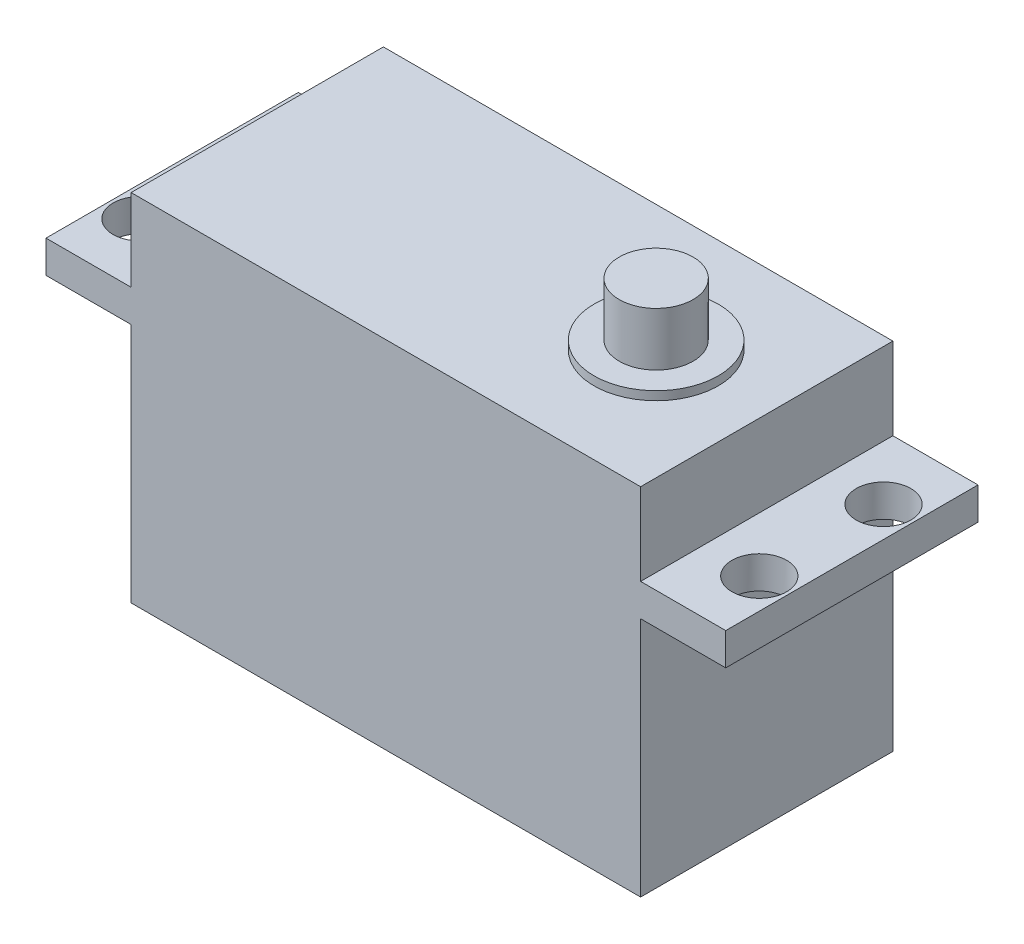
SolidWorks part; units mm, degrees
material "PF"
ref_plane "Front" through (0, 0, 0) normal (0, 0, 1) x (1, 0, 0)
ref_plane "Top" through (0, 0, 0) normal (0, 1, 0) x (1, 0, 0)
ref_plane "Right" through (0, 0, 0) normal (1, 0, 0) x (0, 0, -1)
sketch "Sketch1" plane through (0, 0, 0) normal (0, 0, 1) x (1, 0, 0)
  line L1 (0, 0) -> (41, 0)
  line L2 (0, 0) -> (0, -19.4)
  line L3 (0, -19.4) -> (41, -19.4)
  line L4 (41, 0) -> (41, -19.4)
  dimension "D1" = 41
  dimension "D2" = 19.4
extrude "Boss-Extrude1" add sketch "Sketch1" along normal blind 20.3
sketch "Sketch2" plane through (0, 0, 0) normal (0, 1, 0) x (1, 0, 0)
  line L0 (41, -20.3) -> (0, -20.3) construction
  line L1 (-6.85, -20.3) -> (47.85, -20.3)
  line L2 (-6.85, -20.3) -> (-6.85, 0)
  line L3 (-6.85, 0) -> (47.85, 0)
  line L4 (47.85, -20.3) -> (47.85, 0)
  line L5 (41, 0) -> (0, 0) construction
  line L6 (41, -20.3) -> (41, 0) construction
  dimension "D1" = 54.7
  dimension "D2" = 6.85
extrude "Boss-Extrude2" add sketch "Sketch2" along normal blind 2.6
sketch "Sketch3" plane through (0, 2.6, 0) normal (0, 1, 0) x (1, 0, 0)
  line L0 (-6.85, -20.3) -> (47.85, -20.3) construction
  line L1 (0, -20.3) -> (41, -20.3)
  line L2 (0, -20.3) -> (0, 0)
  line L3 (0, 0) -> (41, 0)
  line L4 (41, -20.3) -> (41, 0)
  line L5 (47.85, 0) -> (-6.85, 0) construction
  line L6 (47.85, -20.3) -> (47.85, 0) construction
  dimension "D1" = 41
  dimension "D2" = 6.85
extrude "Boss-Extrude3" add sketch "Sketch3" along normal blind 6.6
sketch "Sketch4" plane through (0, 2.6, 0) normal (0, 1, 0) x (1, 0, 0)
  line L0 (-6.85, 0) -> (-6.85, -20.3) construction
  line L1 (47.85, -20.3) -> (47.85, 0) construction
  line L2 (47.85, 0) -> (41, 0) construction
  line L3 (0, 0) -> (0, -20.3) construction
  line L4 (0, 0) -> (-6.85, 0) construction
  circle A0 centre (-4.4, -15.15) radius 2.2
  circle A1 centre (-4.4, -5.15) radius 2.2
  circle A2 centre (45.4, -15.15) radius 2.2
  circle A3 centre (45.4, -5.15) radius 2.2
  dimension "D1" = 4.4
  dimension "D2" = 4.4
  dimension "D3" = 4.4
  dimension "D4" = 4.4
  dimension "D5" = 10
  dimension "D6" = 10
  dimension "D7" = 2.45
  dimension "D8" = 2.45
  dimension "D9" = 5.15
  dimension "D10" = 5.15
extrude "Cut-Extrude1" cut sketch "Sketch4" against normal through all
sketch "Sketch5" plane through (0, 9.2, 0) normal (0, 1, 0) x (1, 0, 0)
  line L0 (41, -20.3) -> (41, 0) construction
  line L1 (0, -20.3) -> (41, -20.3) construction
  circle A0 centre (32.1, -10.15) radius 5
  dimension "D3" = 10
  dimension "D1" = 8.9
  dimension "D2" = 10.15
extrude "Boss-Extrude4" add sketch "Sketch5" along normal blind 0.7
sketch "Sketch6" plane through (0, 9.9, 0) normal (0, 1, 0) x (1, 0, 0)
  circle A0 centre (32.1, -10.15) radius 2.97
  dimension "D1" = 5.94
extrude "Boss-Extrude5" add sketch "Sketch6" along normal blind 4.3
